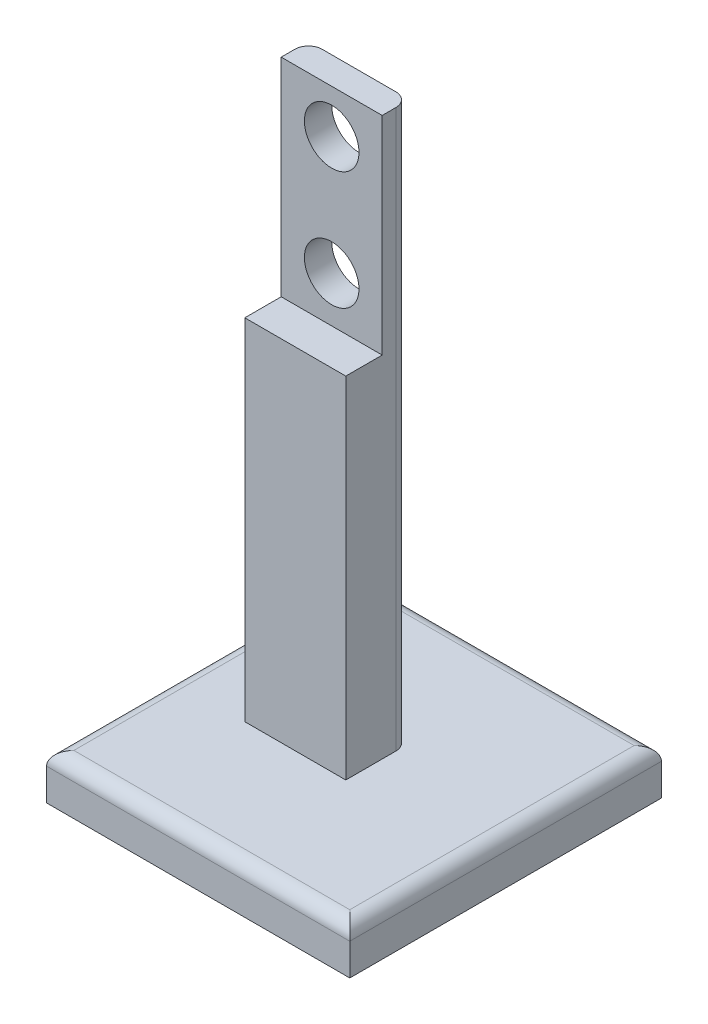
SolidWorks part; units mm, degrees
ref_plane "Front Plane" through (0, 0, 0) normal (0, 0, 1) x (1, 0, 0)
ref_plane "Top Plane" through (0, 0, 0) normal (0, 1, 0) x (1, 0, 0)
ref_plane "Right Plane" through (0, 0, 0) normal (1, 0, 0) x (0, 0, -1)
sketch "Sketch2" plane through (0, 0, 0) normal (0, 0, 1) x (1, 0, 0)
  line L1 (-5.5495, 11.4058) -> (5.5495, 11.4058)
  line L2 (-5.5495, 11.4058) -> (-5.5495, -11.4058)
  line L3 (-5.5495, -11.4058) -> (5.5495, -11.4058)
  line L4 (5.5495, 11.4058) -> (5.5495, -11.4058)
  line L5 (-5.5495, 11.4058) -> (5.5495, -11.4058) construction
  line L6 (-5.5495, -11.4058) -> (5.5495, 11.4058) construction
  point P0 (0, 0)
extrude "Boss-Extrude1" add sketch "Sketch2" along normal blind 3
sketch "Sketch3" plane through (0, 0, 0) normal (0, 0, -1) x (-1, 0, 0)
  line L0 (0, 6.6098) -> (0, -6.3902)
  circle A0 centre (0, 6.6098) radius 3
sketch "Sketch4" plane through (0, 0, 0) normal (0, 0, -1) x (-1, 0, 0)
  circle A0 centre (0, -6.3902) radius 3
extrude "Cut-Extrude1" cut sketch "Sketch3" against normal blind 3 contours A0
extrude "Cut-Extrude2" cut sketch "Sketch4" against normal blind 3 contours A0
sketch "Sketch5" plane through (0, 0, 0) normal (0, 0, -1) x (-1, 0, 0)
  line L1 (-5.5495, -11.4058) -> (5.5495, -11.4058)
  line L2 (-5.5495, -11.4058) -> (-5.5495, -54.8559)
  line L3 (-5.5495, -54.8559) -> (5.5495, -54.8559)
  line L4 (5.5495, -11.4058) -> (5.5495, -54.8559)
extrude "Boss-Extrude2" add sketch "Sketch5" against normal blind 7
sketch "Sketch6" plane through (0, -54.8559, 0) normal (0, -1, 0) x (-1, 0, 0)
  line L1 (-19.6148, 13.6276) -> (13.7113, 13.6276)
  line L2 (-19.6148, 13.6276) -> (-19.6148, -20.6278)
  line L3 (-19.6148, -20.6278) -> (13.7113, -20.6278)
  line L4 (13.7113, 13.6276) -> (13.7113, -20.6278)
  line L5 (-19.6148, 13.6276) -> (13.7113, -20.6278) construction
  line L6 (-19.6148, -20.6278) -> (13.7113, 13.6276) construction
  point P0 (-2.9518, -3.5001)
extrude "Boss-Extrude3" add sketch "Sketch6" against normal blind 5
fillet "Fillet1" radius 1.5 4 edges at (2.9518, -49.8559, 20.6278) (-13.7113, -49.8559, 3.5001) (2.9518, -49.8559, -13.6276) (19.6148, -49.8559, 3.5001)
fillet "Fillet2" radius 1.5 2 edges at (5.5495, -19.225, 0) (-5.5495, -19.225, 0)
